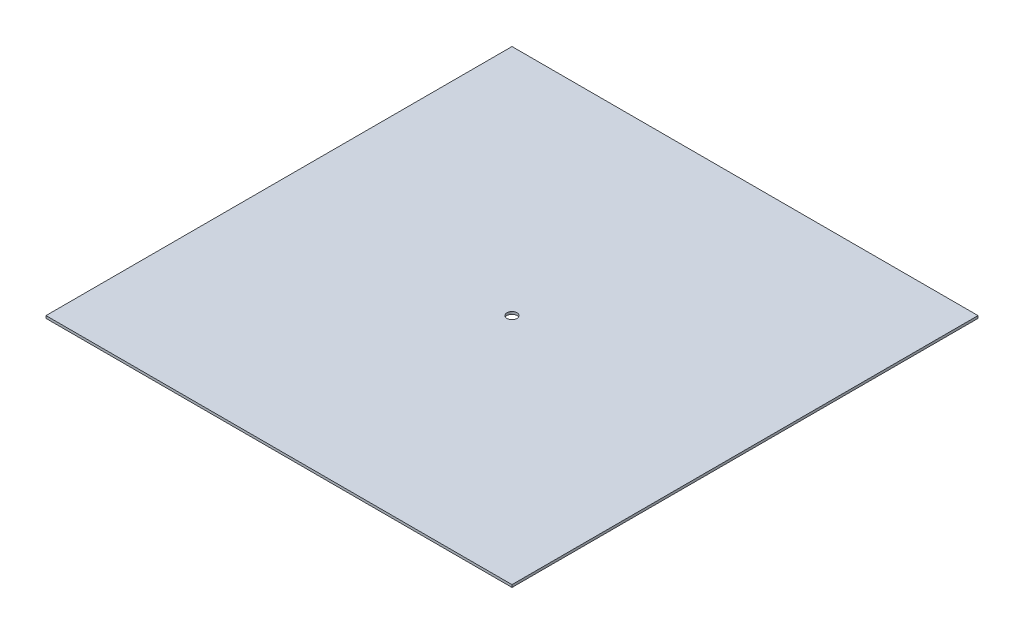
SolidWorks part; units mm, degrees
material "AISI 304"
ref_plane "Front Plane" through (0, 0, 0) normal (0, 0, 1) x (1, 0, 0)
ref_plane "Top Plane" through (0, 0, 0) normal (0, 1, 0) x (1, 0, 0)
ref_plane "Right Plane" through (0, 0, 0) normal (1, 0, 0) x (0, 0, -1)
sketch "Sketch1" plane through (0, 0, 0) normal (0, 1, 0) x (1, 0, 0)
  line L1 (152.4, 152.4) -> (-152.4, 152.4)
  line L2 (152.4, 152.4) -> (152.4, -152.4)
  line L3 (152.4, -152.4) -> (-152.4, -152.4)
  line L4 (-152.4, 152.4) -> (-152.4, -152.4)
  line L5 (0, -152.4) -> (0, 152.4) construction
  line L6 (152.4, 0) -> (-152.4, 0) construction
  point P0 (0, 0)
  dimension "D1" = 304.8
  dimension "D2" = 304.8
extrude "Boss-Extrude1" add sketch "Sketch1" along normal blind 1.6256
hole_wizard "1/4 Clearance Hole1" positions "Sketch3" profile "Sketch2" hole size "1/4" standard "ANSI Inch" end condition through all
sketch "Sketch3" plane through (0, 1.6256, 0) normal (0, 1, 0) x (1, 0, 0)
  point P0 (0, 0)
sketch "Sketch2" plane through (0, 1.6256, 0) normal (1, 0, 0) x (0, 0, 1)
  line L0 (0, 0) -> (0, 1.6256)
  line L1 (0, 1.6256) -> (3.2639, 1.6256)
  line L2 (3.2639, 1.6256) -> (3.2639, 0)
  line L5 (3.2639, 0) -> (0, 0)
  line L11 (0, -6.35) -> (0, 107.95) construction
  dimension "Thru Hole Dia." = 6.5278
  dimension "Thru Hole Depth" = 1.6256
